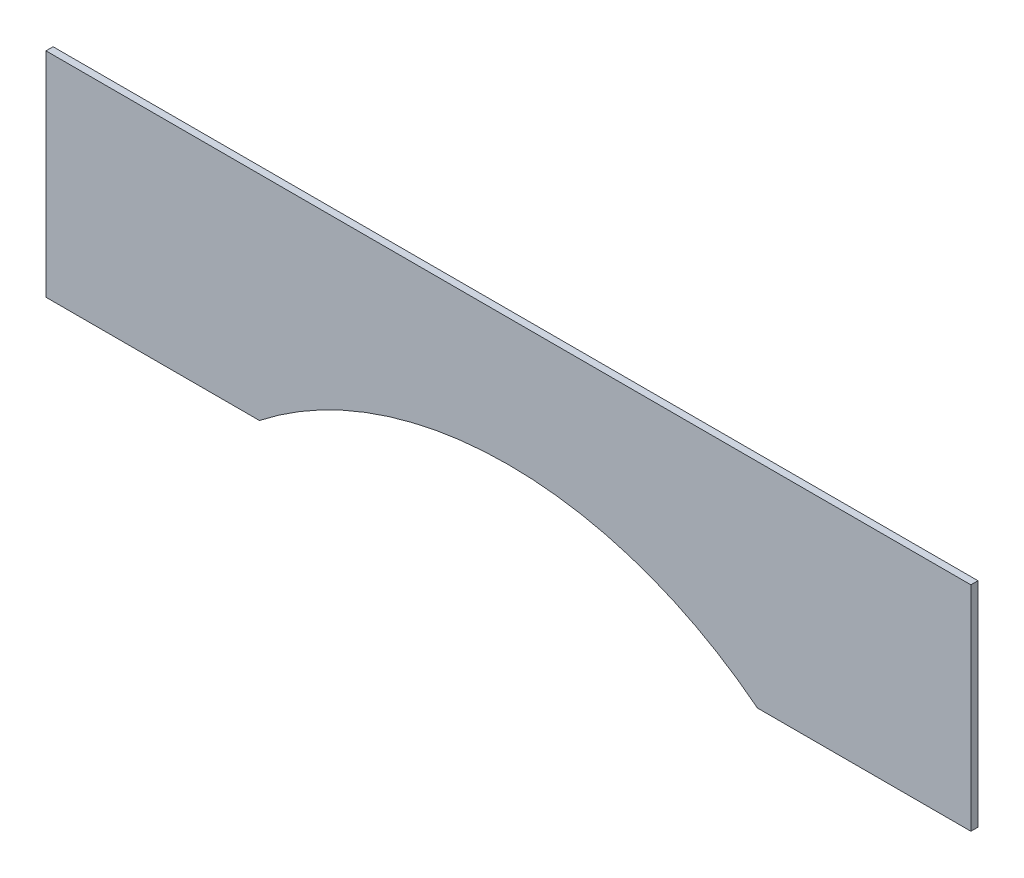
SolidWorks part; units mm, degrees
ref_plane "Front Plane" through (0, 0, 0) normal (0, 0, 1) x (1, 0, 0)
ref_plane "Top Plane" through (0, 0, 0) normal (0, 1, 0) x (1, 0, 0)
ref_plane "Right Plane" through (0, 0, 0) normal (1, 0, 0) x (0, 0, -1)
sketch "Sketch1" plane through (0, 0, 0) normal (0, 0, 1) x (1, 0, 0)
  line L0 (0, 0) -> (76.2, 0)
  line L2 (0, 0) -> (0, 76.2)
  line L3 (0, 76.2) -> (330.2, 76.2)
  line L4 (330.2, 0) -> (330.2, 76.2)
  line L5 (330.2, 0) -> (254, 0)
  arc A2 (76.2, 0) -> (254, 0) centre (165.1, -112.8801) cw
  dimension "D1" = 76.2
  dimension "D2" = 76.2
  dimension "D3" = 330.2
extrude "Boss-Extrude1" add sketch "Sketch1" along normal blind 2.54 contours L5 A2 L0 L2 L3 L4
